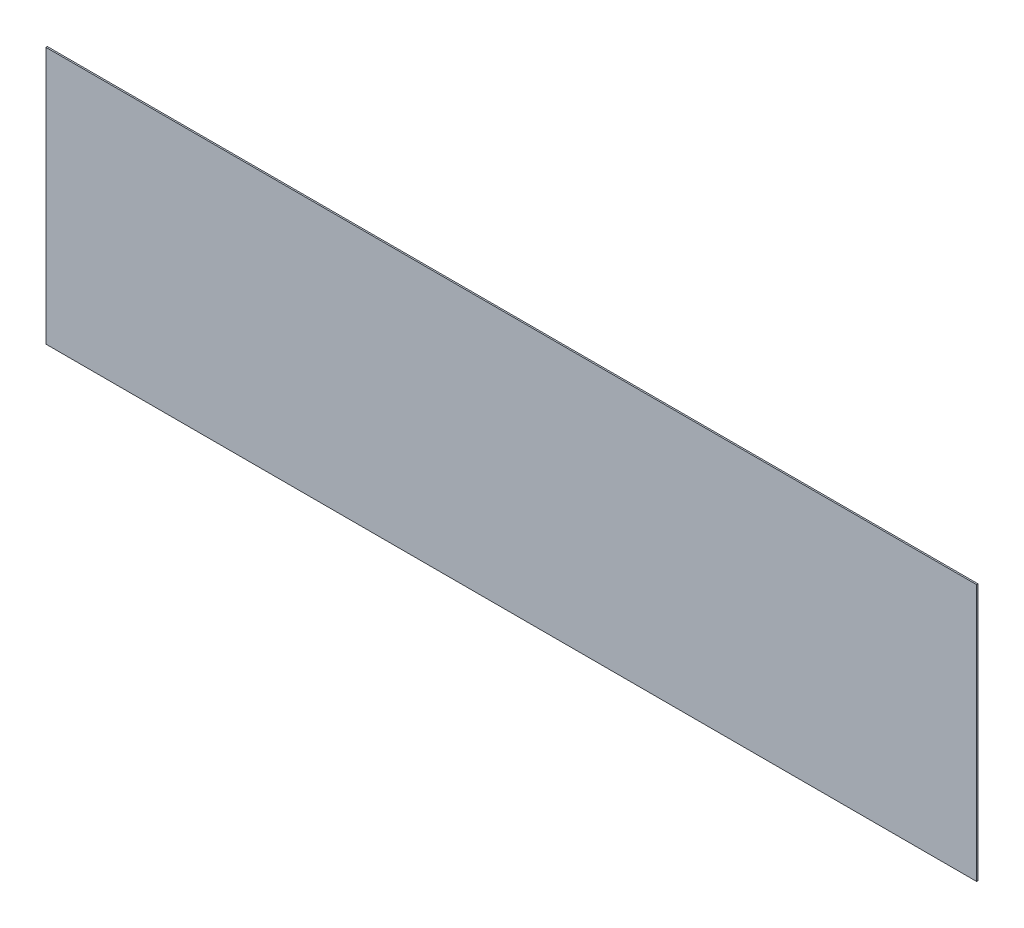
SolidWorks part; units mm, degrees
ref_plane "Front Plane" through (0, 0, 0) normal (0, 0, 1) x (1, 0, 0)
ref_plane "Top Plane" through (0, 0, 0) normal (0, 1, 0) x (1, 0, 0)
ref_plane "Right Plane" through (0, 0, 0) normal (1, 0, 0) x (0, 0, -1)
other "Configuration Table"
sketch "Sketch1" plane through (0, 0, 0) normal (0, 0, 1) x (1, 0, 0)
  line L1 (702, 1469) -> (1350, 1469)
  line L2 (702, 1469) -> (702, 1648)
  line L3 (702, 1648) -> (1350, 1648)
  line L4 (1350, 1469) -> (1350, 1648)
extrude "DET_arka_ic_sac_1" add sketch "Sketch1" against normal blind 1 from offset 757.5 separate body
